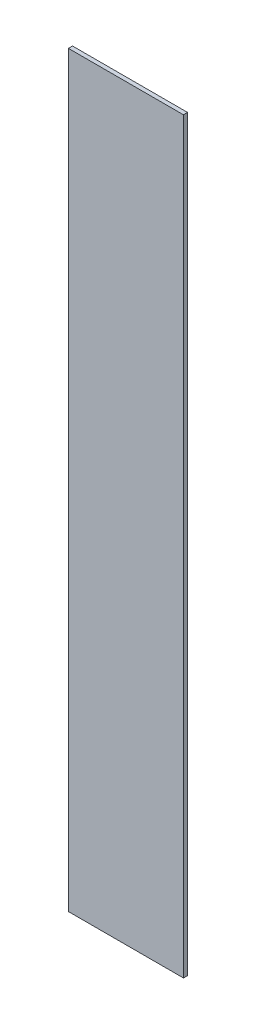
SolidWorks part; units mm, degrees
ref_plane "Front Plane" through (0, 0, 0) normal (0, 0, 1) x (1, 0, 0)
ref_plane "Top Plane" through (0, 0, 0) normal (0, 1, 0) x (1, 0, 0)
ref_plane "Right Plane" through (0, 0, 0) normal (1, 0, 0) x (0, 0, -1)
other "Configuration Table"
sketch "Sketch1" plane through (0, 0, 0) normal (0, 0, 1) x (1, 0, 0)
  line L1 (623, 1404) -> (651, 1404)
  line L2 (623, 1404) -> (623, 1586)
  line L3 (623, 1586) -> (651, 1586)
  line L4 (651, 1404) -> (651, 1586)
extrude "PACK_sarjor_kapisi_kulp_cukuru_1" add sketch "Sketch1" along normal blind 1 from offset 26 separate body
